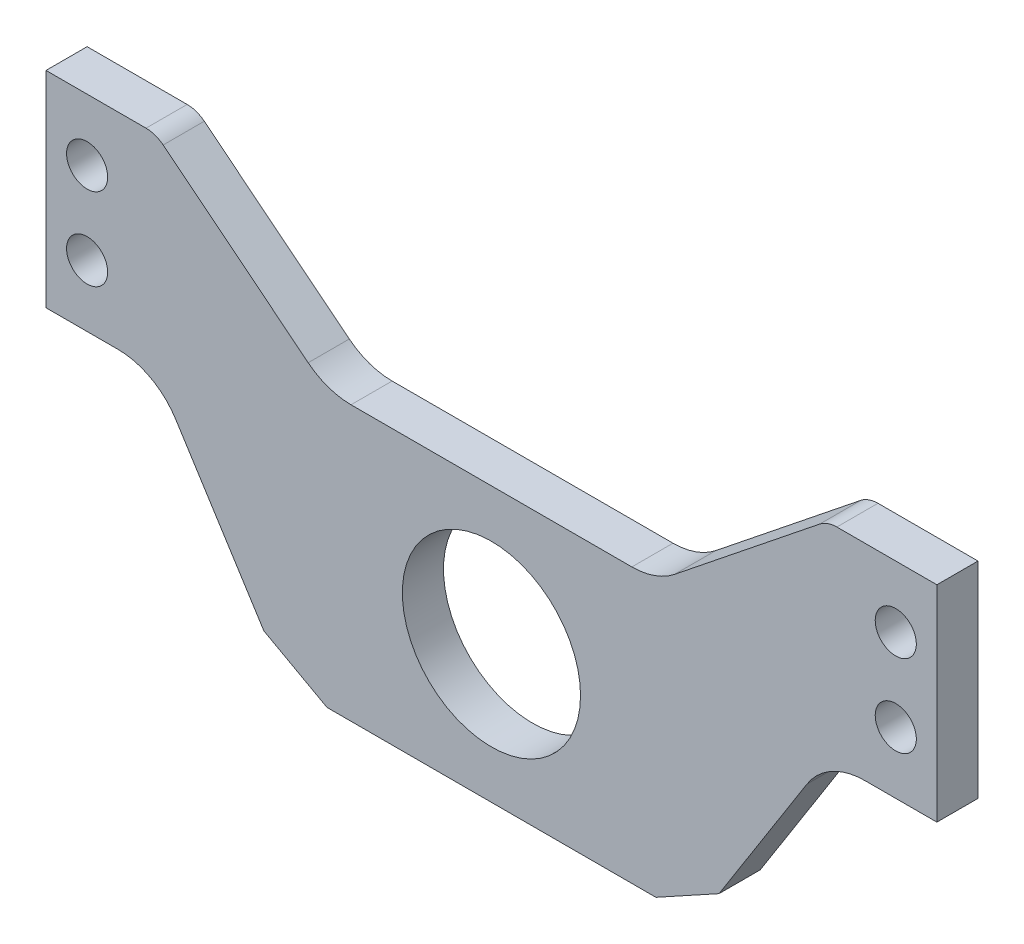
SolidWorks part; units mm, degrees
material "6061-T4 (SS)"
ref_plane "前视基准面" through (0, 0, 0) normal (0, 0, 1) x (1, 0, 0)
ref_plane "上视基准面" through (0, 0, 0) normal (0, 1, 0) x (1, 0, 0)
ref_plane "右视基准面" through (0, 0, 0) normal (1, 0, 0) x (0, 0, -1)
sketch "草图1" plane through (0, 0, 0) normal (0, 0, 1) x (1, 0, 0)
  line L0 (15, -10) -> (-15, -10)
  line L1 (0, 23.5463) -> (0, -22.3572) construction
  line L2 (-15, -10) -> (-24.5, 5)
  line L3 (12, 10) -> (-12, 10)
  line L4 (-12, 10) -> (-24.5, 20)
  line L5 (32.5, 5) -> (24.5, 5)
  line L6 (-24.5, 20) -> (-32.5, 20)
  line L7 (-32.5, 20) -> (-32.5, 5)
  line L8 (-32.5, 5) -> (-24.5, 5)
  line L9 (32.5, 20) -> (32.5, 5)
  line L10 (24.5, 20) -> (32.5, 20)
  line L11 (12, 10) -> (24.5, 20)
  line L12 (15, -10) -> (24.5, 5)
  line L13 (-29.5, 31.7505) -> (-29.5, -0.6388) construction
  line L14 (-32.538, 12.5) -> (-18.6108, 12.5) construction
  circle A0 centre (0, 0) radius 6.5
  circle A1 centre (-29.5, 15.5) radius 1.5
  circle A2 centre (29.5, 9.5) radius 1.5
  circle A3 centre (-29.5, 9.5) radius 1.5
  circle A4 centre (29.5, 15.5) radius 1.5
  point P18 (0, 10)
  point P19 (0, -10)
  dimension "D1" = 13
  dimension "D12" = 3
  dimension "D14" = 3
  dimension "D15" = 3
  dimension "D2" = 15
  dimension "D3" = 20
  dimension "D4" = 10
  dimension "D5" = 12
  dimension "D6" = 65
  dimension "D7" = 20
  dimension "D8" = 15
  dimension "D9" = 8
  dimension "D10" = 8
  dimension "D11" = 3
  dimension "D13" = 7.5
extrude "凸台-拉伸1" add sketch "草图1" along normal blind 3
fillet "圆角1" radius 5 2 edges at (12, 10, 1.5) (-12, 10, 1.5)
chamfer "倒角1" distance 3 distance2 3 2 edges at (15, -10, 1.5) (-15, -10, 1.5)
fillet "圆角3" radius 5 2 edges at (24.5, 5, 1.5) (-24.5, 5, 1.5)
fillet "圆角4" radius 2 2 edges at (24.5, 20, 1.5) (-24.5, 20, 1.5)
